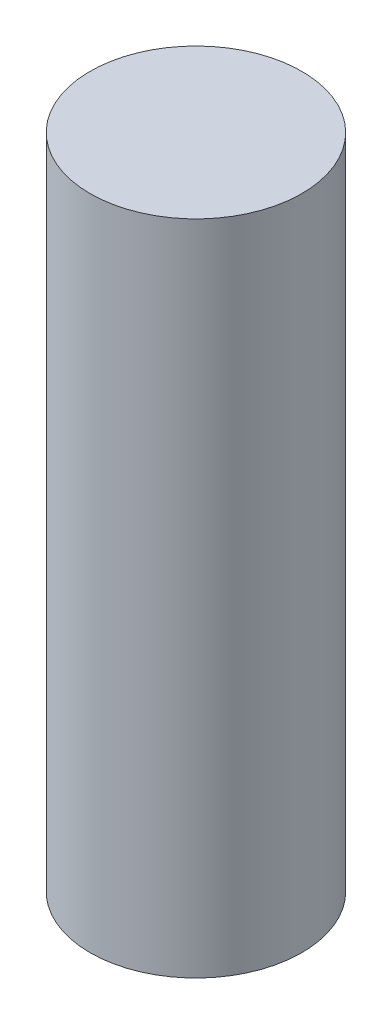
SolidWorks part; units mm, degrees
material "Butt splice"
ref_plane "Front Plane" through (0, 0, 0) normal (0, 0, 1) x (1, 0, 0)
ref_plane "Top Plane" through (0, 0, 0) normal (0, 1, 0) x (1, 0, 0)
ref_plane "Right Plane" through (0, 0, 0) normal (1, 0, 0) x (0, 0, -1)
sketch "Sketch1" plane through (0, 0, 0) normal (0, 1, 0) x (1, 0, 0)
  circle A0 centre (0, 0) radius 12
  dimension "D1" = 24
extrude "Boss-Extrude1" add sketch "Sketch1" along normal blind 74.5
